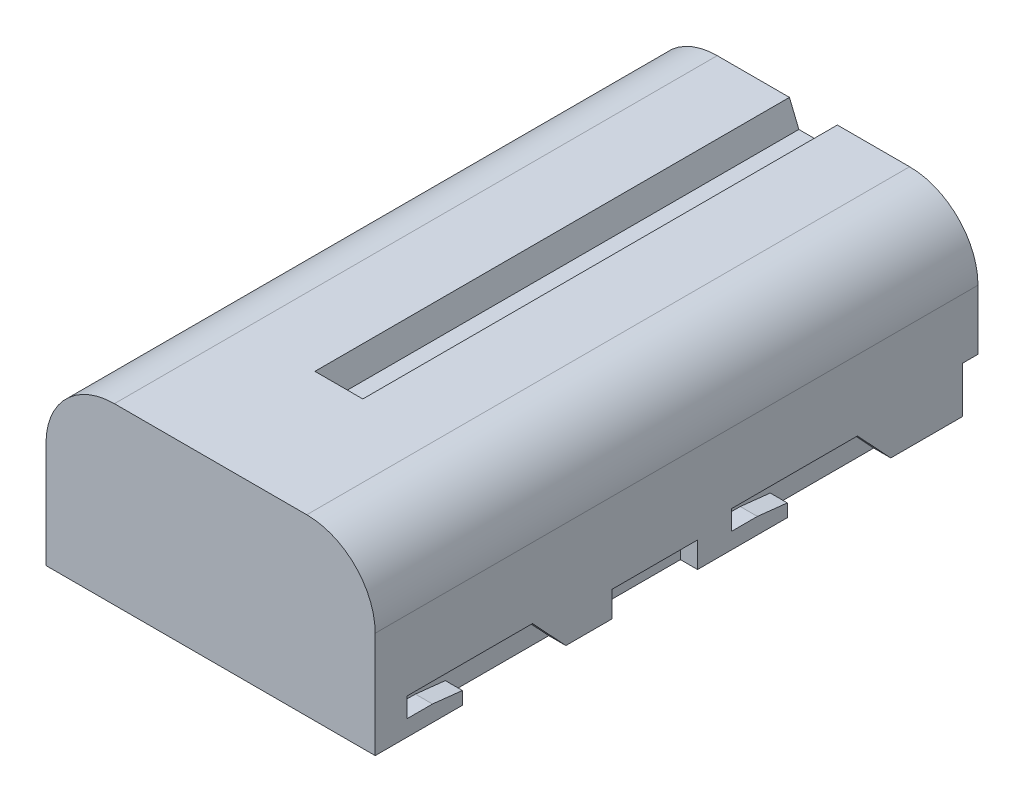
SolidWorks part; units mm, degrees
ref_plane "前视基准面" through (0, 0, 0) normal (0, 0, 1) x (1, 0, 0)
ref_plane "上视基准面" through (0, 0, 0) normal (0, 1, 0) x (1, 0, 0)
ref_plane "右视基准面" through (0, 0, 0) normal (1, 0, 0) x (0, 0, -1)
sketch "草图1" plane through (0, 0, 0) normal (0, 0, 1) x (1, 0, 0)
  line L0 (0, 0) -> (0, 2.2) construction
  line L1 (-19.25, 2.2) -> (19.25, 2.2)
  line L2 (-19.25, 2.2) -> (-19.25, -10.2)
  line L3 (-19.25, -10.2) -> (19.25, -10.2)
  line L4 (19.25, 2.2) -> (19.25, -10.2)
  line L5 (-11.25, 10.2) -> (11.25, 10.2)
  line L6 (-11.25, 10.2) -> (-11.25, 2.2)
  line L7 (-11.25, 2.2) -> (11.25, 2.2)
  line L8 (11.25, 10.2) -> (11.25, 2.2)
  circle A0 centre (-11.25, 2.2) radius 8
  circle A1 centre (11.25, 2.2) radius 8
  point P8 (0, 0)
  dimension "D1" = 2.2
  dimension "D2" = 10.2
  dimension "D3" = 38.5
  dimension "D5" = 8
extrude "凸台-拉伸1" add sketch "草图1" along normal mid plane 70.5
sketch "草图2" plane through (0, 0, -35.25) normal (0, 0, -1) x (-1, 0, 0)
  line L0 (0, 0) -> (0, 7.5) construction
  line L1 (-2.8, 10.2) -> (2.8, 10.2)
  line L2 (2.8, 10.2) -> (1.7, 7.5)
  line L3 (1.7, 7.5) -> (-1.7, 7.5)
  line L4 (-1.7, 7.5) -> (-2.8, 10.2)
  point P0 (0, 0)
  dimension "D1" = 3.4
  dimension "D2" = 5.6
  dimension "D3" = 2.7
  dimension "D4" = 7.5
extrude "切除-拉伸1" cut sketch "草图2" against normal blind 55.5
sketch "草图3" plane through (-19.25, 0, 0) normal (-1, 0, 0) x (0, 0, 1)
  line L0 (-35.25, 2.2) -> (-35.25, -10.2) construction
  line L1 (-35.25, -10.2) -> (-33.45, -10.2)
  line L2 (-35.25, -10.2) -> (-35.25, -4.8)
  line L3 (-35.25, -4.8) -> (-33.45, -4.8)
  line L4 (-33.45, -10.2) -> (-33.45, -4.8)
  line L5 (35.25, -10.2) -> (-35.25, -10.2) construction
  line L6 (-25.05, -10.2) -> (-21.15, -6.0178)
  line L7 (-21.15, -6.0178) -> (-6.45, -6.0178)
  line L8 (-6.45, -6.0178) -> (-6.45, -8.3178)
  line L9 (-6.45, -8.3178) -> (-9.45, -8.3178)
  line L10 (-9.45, -8.3178) -> (-12.95, -8.7)
  line L11 (-12.95, -8.7) -> (-12.95, -10.2)
  line L12 (-12.95, -10.2) -> (-25.05, -10.2)
  line L14 (-2.45, -7.2) -> (7.55, -7.2)
  line L15 (-2.45, -7.2) -> (-2.45, -10.2)
  line L16 (-2.45, -10.2) -> (7.55, -10.2)
  line L17 (7.55, -7.2) -> (7.55, -10.2)
  line L24 (12.95, -10.2) -> (16.85, -6.0178)
  line L25 (16.85, -6.0178) -> (31.55, -6.0178)
  line L26 (31.55, -6.0178) -> (31.55, -8.3178)
  line L27 (31.55, -8.3178) -> (28.55, -8.3178)
  line L28 (28.55, -8.3178) -> (25.05, -8.7)
  line L29 (25.05, -8.7) -> (25.05, -10.2)
  line L30 (25.05, -10.2) -> (12.95, -10.2)
  dimension "D1" = 5.4
  dimension "D2" = 1.8
  dimension "D3" = 8.4
  dimension "D4" = 47
  dimension "D5" = 3.9
  dimension "D6" = 14.7
  dimension "D7" = 2.3
  dimension "D8" = 3
  dimension "D9" = 1.5
  dimension "D10" = 12.1
  dimension "D11" = 3.9
  dimension "D12" = 14.7
  dimension "D13" = 3
  dimension "D14" = 1.5
  dimension "D15" = 12.1
  dimension "D16" = 47
  dimension "D17" = 38
  dimension "D18" = 2.3
  dimension "D19" = 31
  dimension "D20" = 10
  dimension "D21" = 3
extrude "切除-拉伸2" cut sketch "草图3" against normal blind 2
sketch "草图4" plane through (-17.25, 0, 0) normal (-1, 0, 0) x (0, 0, 1)
  line L4 (-35.25, -4.8) -> (-35.25, -10.2)
  line L5 (-35.25, -10.2) -> (-33.45, -10.2)
  line L6 (-33.45, -10.2) -> (-33.45, -4.8)
  line L7 (-33.45, -4.8) -> (-35.25, -4.8)
  line L8 (-35.25, -4.8) -> (-35.25, -10.2)
  line L9 (-35.25, -10.2) -> (-33.45, -10.2)
  line L10 (-33.45, -10.2) -> (-33.45, -4.8)
  line L11 (-33.45, -4.8) -> (-35.25, -4.8)
  dimension "D1" = 0
extrude "切除-拉伸3" cut sketch "草图4" against normal blind 4.5
mirror "镜向1" about plane through (0, 0, 0) normal (1, 0, 0) of "切除-拉伸3", "切除-拉伸2", "切除-拉伸1"
